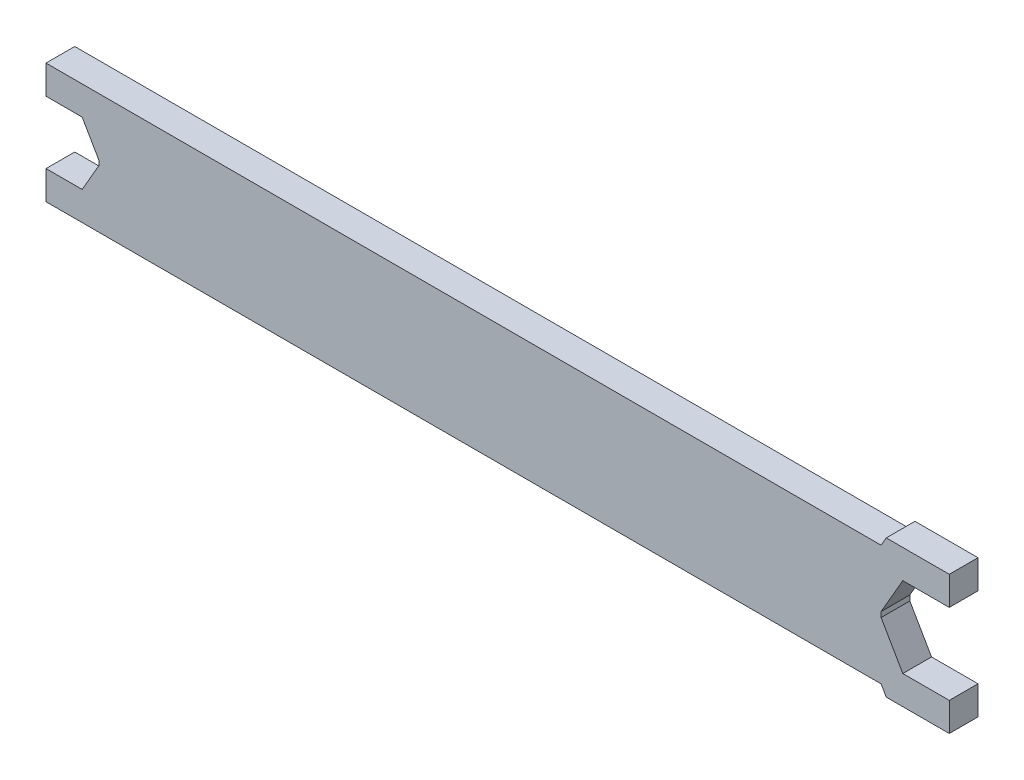
SolidWorks part; units mm, degrees
ref_plane "Front Plane" through (0, 0, 0) normal (0, 0, 1) x (1, 0, 0)
ref_plane "Top Plane" through (0, 0, 0) normal (0, 1, 0) x (1, 0, 0)
ref_plane "Right Plane" through (0, 0, 0) normal (1, 0, 0) x (0, 0, -1)
sketch "Sketch1" plane through (0, 0, 0) normal (0, 0, 1) x (1, 0, 0)
  line L0 (0, 0) -> (76.2, 0) construction
  line L1 (6.1298, 0) -> (3.0649, 5.3086) construction
  line L2 (3.1969, 0) -> (1.5985, 2.7686)
  line L3 (1.5985, 2.7686) -> (-1.5985, 2.7686)
  line L4 (-1.5985, 2.7686) -> (-3.1969, 0) construction
  line L5 (-3.1969, 0) -> (-1.5985, -2.7686) construction
  line L6 (-1.5985, -2.7686) -> (1.5985, -2.7686)
  line L7 (1.5985, -2.7686) -> (3.1969, 0)
  line L8 (3.0649, 5.3086) -> (-1.5985, 5.3086)
  line L11 (-1.5985, -5.3086) -> (3.0649, -5.3086)
  line L12 (3.0649, -5.3086) -> (6.1298, 0) construction
  line L13 (-1.5985, 2.7686) -> (-1.5985, 5.3086)
  line L14 (-1.5985, -2.7686) -> (-1.5985, -5.3086)
  line L15 (-1.5985, 5.3086) -> (-1.5985, 2.7686)
  line L16 (-3.0649, 5.3086) -> (-6.1298, 0) construction
  line L17 (-6.1298, 0) -> (-3.0649, -5.3086) construction
  line L18 (-3.0649, -5.3086) -> (3.0649, -5.3086) construction
  line L19 (3.0649, 5.3086) -> (-3.0649, 5.3086) construction
  line L20 (-1.5985, -2.7686) -> (-1.5985, -5.3086)
  line L21 (78.2531, 6.096) -> (72.6805, 6.096)
  line L22 (80.3061, 0) -> (78.2531, 3.556) construction
  line L23 (78.2531, 3.556) -> (74.1469, 3.556)
  line L24 (74.1469, 3.556) -> (72.0939, 0)
  line L25 (72.0939, 0) -> (74.1469, -3.556)
  line L26 (74.1469, -3.556) -> (78.2531, -3.556)
  line L27 (78.2531, -3.556) -> (80.3061, 0) construction
  line L28 (72.6805, 6.096) -> (69.1609, 0) construction
  line L29 (69.1609, 0) -> (72.6805, -6.096) construction
  line L30 (72.6805, -6.096) -> (78.2531, -6.096)
  line L33 (78.2531, 3.556) -> (78.2531, 6.096)
  line L34 (78.2531, -3.556) -> (78.2531, -6.096)
  line L35 (4.5974, -2.6543) -> (70.6934, -2.6543)
  line L36 (83.2391, 0) -> (79.7195, 6.096) construction
  line L37 (79.7195, -6.096) -> (83.2391, 0) construction
  line L38 (72.6805, -6.096) -> (79.7195, -6.096) construction
  line L39 (79.7195, 6.096) -> (72.6805, 6.096) construction
  line L40 (4.5974, 2.6543) -> (70.6934, 2.6543)
  line L41 (3.0649, 5.3086) -> (4.5974, 2.6543)
  line L42 (4.5974, -2.6543) -> (3.0649, -5.3086)
  line L43 (70.6934, -2.6543) -> (72.6805, -6.096)
  line L44 (70.6934, 2.6543) -> (72.6805, 6.096)
  circle A0 centre (0, 0) radius 2.7686 construction
  circle A1 centre (76.2, 0) radius 3.556 construction
  dimension "D1" = 5.5372
  dimension "D3" = 76.2
  dimension "D4" = 7.112
  dimension "D2" = 2.54
  dimension "D5" = 2.54
extrude "Boss-Extrude1" add sketch "Sketch1" along normal blind 2.54 contours L44 L40 L41 L8 L13 L3 L2 L7 L6 L14 L11 L42 L35 L43 L30 L34 L26 L25 L24 L23 L33 L21
sketch "Sketch3" plane through (0, 0, 2.54) normal (0, 0, 1) x (1, 0, 0)
  line L0 (70.6934, 2.6543) -> (72.6805, 6.096) construction
  line L1 (3.0649, 5.3086) -> (72.2259, 5.3086)
  line L2 (3.0649, 5.3086) -> (3.0649, -5.3086)
  line L3 (3.0649, -5.3086) -> (72.2259, -5.3086)
  line L4 (72.2259, 5.3086) -> (72.2259, -5.3086)
  point P5 (3.0649, -9.5553)
  point P6 (3.0649, -5.3086)
  point P8 (0, 0)
extrude "Boss-Extrude2" add sketch "Sketch3" against normal up to surface (2.54 mm away) up to face at (37.976, 0, 0)
